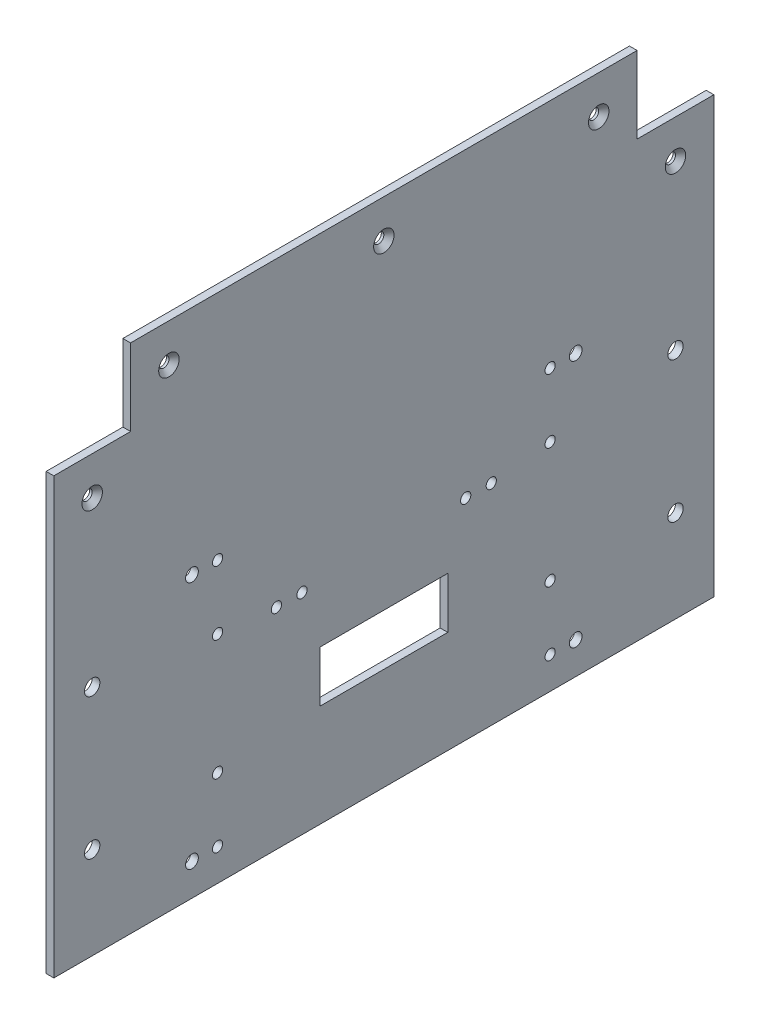
SolidWorks part; units mm, degrees
material "1060 合金"
ref_plane "前视基准面" through (0, 0, 0) normal (0, 0, 1) x (1, 0, 0)
ref_plane "上视基准面" through (0, 0, 0) normal (0, 1, 0) x (1, 0, 0)
ref_plane "右视基准面" through (0, 0, 0) normal (1, 0, 0) x (0, 0, -1)
sketch "草图1" plane through (0, 0, 0) normal (1, 0, 0) x (0, 0, -1)
  line L1 (-129, 100) -> (129, 100)
  line L2 (-129, 100) -> (-129, -100)
  line L3 (-129, -100) -> (129, -100)
  line L4 (129, 100) -> (129, -100)
  point P4 (0, 100)
  point P6 (129, 0)
  dimension "D1" = 258
  dimension "D2" = 200
extrude "凸台-拉伸1" add sketch "草图1" along normal blind 3
sketch "草图2" plane through (0, 0, 0) normal (1, 0, 0) x (0, 0, -1)
  line L0 (0, 64) -> (0, -66) construction
  line L1 (129, 100) -> (-129, 100) construction
  line L2 (-129, 100) -> (-129, -100) construction
  line L3 (-255, -70) -> (255, -70) construction
  line L4 (129, 70) -> (99, 70)
  line L5 (-129, 100) -> (-99, 100)
  line L7 (-25, -40) -> (25, -40)
  line L8 (-129, -100) -> (129, -100) construction
  line L9 (-129, 100) -> (-129, 70)
  line L10 (-129, 70) -> (-99, 70)
  line L11 (-99, 100) -> (-99, 70)
  line L12 (99, 100) -> (99, 70)
  line L13 (129, 100) -> (99, 100)
  line L14 (129, 100) -> (129, 70)
  line L15 (-25, -40) -> (-25, -60)
  line L16 (-25, -60) -> (25, -60)
  line L17 (25, -40) -> (25, -60)
  circle A8 centre (-114, -9) radius 3
  circle A10 centre (-114, -64) radius 3
  circle A13 centre (114, -64) radius 3
  circle A15 centre (114, -9) radius 3
  circle A16 centre (-32, -18) radius 2
  circle A17 centre (32, -18) radius 2
  circle A18 centre (-42, -18) radius 2
  circle A19 centre (42, -18) radius 2
  circle A20 centre (-75, -87.5) radius 2.5
  circle A21 centre (-75, 9.5) radius 2.5
  circle A22 centre (75, -87.5) radius 2.5
  circle A23 centre (75, 9.5) radius 2.5
  circle A24 centre (-65, 9.5) radius 2
  circle A25 centre (-65, -15.5) radius 2
  circle A26 centre (-65, -62.5) radius 2
  circle A27 centre (-65, -87.5) radius 2
  circle A28 centre (65, -87.5) radius 2
  circle A29 centre (65, -62.5) radius 2
  circle A30 centre (65, -15.5) radius 2
  circle A31 centre (65, 9.5) radius 2
  circle A32 centre (-114, 55) radius 2
  circle A33 centre (-84, 85) radius 2
  circle A34 centre (0, 85) radius 2
  circle A35 centre (84, 85) radius 2
  circle A36 centre (114, 55) radius 2
  dimension "D2" = 36
  dimension "D9" = 4
  dimension "D15" = 5
  dimension "D17" = 30
  dimension "D4" = 6
  dimension "D7" = 4
  dimension "D21" = 4
  dimension "D1" = 30
  dimension "D3" = 15
  dimension "D5" = 10
  dimension "D6" = 25
  dimension "D8" = 55
  dimension "D10" = 64
  dimension "D11" = 118
  dimension "D12" = 10
  dimension "D13" = 12.5
  dimension "D14" = 54
  dimension "D16" = 97
  dimension "D18" = 30
  dimension "D19" = 25
  dimension "D20" = 15
  dimension "D22" = 15
  dimension "D23" = 15
  dimension "D24" = 15
  dimension "D25" = 40
  dimension "D26" = 20
  dimension "D27" = 50
  dimension "D28" = 25
extrude "切除-拉伸2" cut sketch "草图2" along normal blind 3
chamfer "倒角2" distance 2 angle 45 5 edges at (3, 55, -112) (3, 85, -82) (3, 85, -2) (3, 85, 82) (3, 55, 112)
